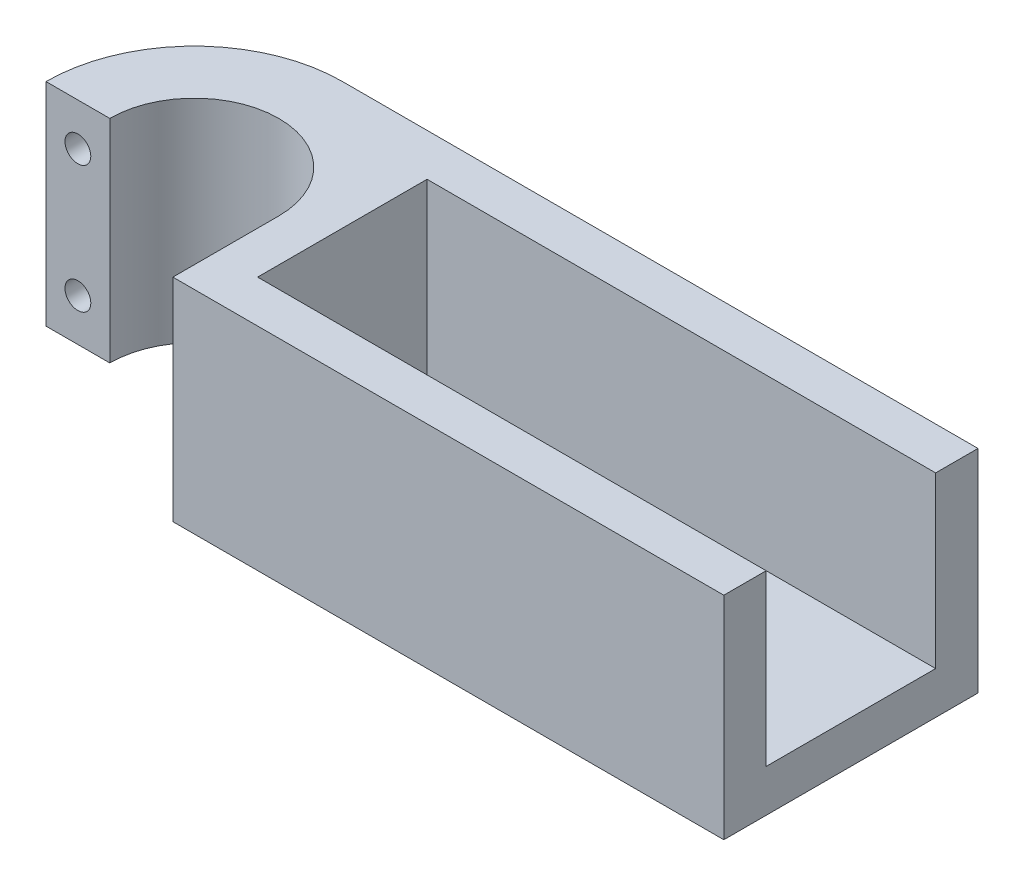
SolidWorks part; units mm, degrees
ref_plane "Front Plane" through (0, 0, 0) normal (0, 0, 1) x (1, 0, 0)
ref_plane "Top Plane" through (0, 0, 0) normal (0, 1, 0) x (1, 0, 0)
ref_plane "Right Plane" through (0, 0, 0) normal (1, 0, 0) x (0, 0, -1)
sketch "Sketch2" plane through (0, 0, 0) normal (0, 1, 0) x (1, 0, 0)
  line L1 (-75, 30) -> (75, 30)
  line L4 (75, 30) -> (75, -30)
  line L5 (-55.05, -30) -> (75, -30)
  line L8 (-55.05, -5) -> (-55.05, -30)
  line L9 (-94.95, -5) -> (-110, -5)
  arc A0 (-75, 30) -> (-110, -5) centre (-75, -5) ccw
  arc A1 (-55.05, -5) -> (-94.95, -5) centre (-75, -5) ccw
  point P0 (0, 0)
  dimension "D3" = 39.9
  dimension "D1" = 15.05
  dimension "D2" = 150
  dimension "D4" = 60
extrude "Boss-Extrude1" add sketch "Sketch2" along normal blind 50 contours L1 L4 L5 L8 A1 L9 A0
sketch "Sketch3" plane through (0, 0, 5) normal (0, 0, 1) x (1, 0, 0)
  line L0 (-102.475, 50) -> (-102.475, 0) construction
  line L1 (-94.95, 50) -> (-110, 50) construction
  line L2 (-94.95, 0) -> (-110, 0) construction
  circle A0 centre (-102.475, 40) radius 3.05
  circle A1 centre (-102.475, 10) radius 3.05
  dimension "D1" = 6.1
  dimension "D2" = 6.1
  dimension "D3" = 30
  dimension "D4" = 10
extrude "Cut-Extrude1" cut sketch "Sketch3" against normal blind 7.5 contours A0
sketch "Sketch4" plane through (0, 0, -2.5) normal (0, 0, 1) x (1, 0, 0)
  circle A0 centre (-102.475, 40) radius 5.25
  circle A1 centre (-102.475, 10) radius 5.25
  circle A2 centre (-102.475, 40) radius 3.05 construction
  circle A3 centre (-102.475, 10) radius 3.05 construction
  dimension "D1" = 10.5
  dimension "D2" = 10.5
extrude "Cut-Extrude2" cut sketch "Sketch4" against normal blind 50
sketch "Sketch5" plane through (0, 50, 0) normal (0, 1, 0) x (1, 0, 0)
  line L0 (103.478, 20) -> (103.478, -20)
  line L1 (103.478, 20) -> (-45.05, 20)
  line L2 (103.478, -20) -> (-45.05, -20)
  line L3 (-45.05, 20) -> (-45.05, -20)
  line L4 (-75, 30) -> (75, 30) construction
  line L5 (-55.05, -30) -> (75, -30) construction
  line L7 (-55.05, -5) -> (-55.05, -30) construction
  point P6 (0, 30)
  dimension "D1" = 10
  dimension "D2" = 10
  dimension "D3" = 10
extrude "Cut-Extrude3" cut sketch "Sketch5" against normal blind 40 contours L0 L2 L3 L1
